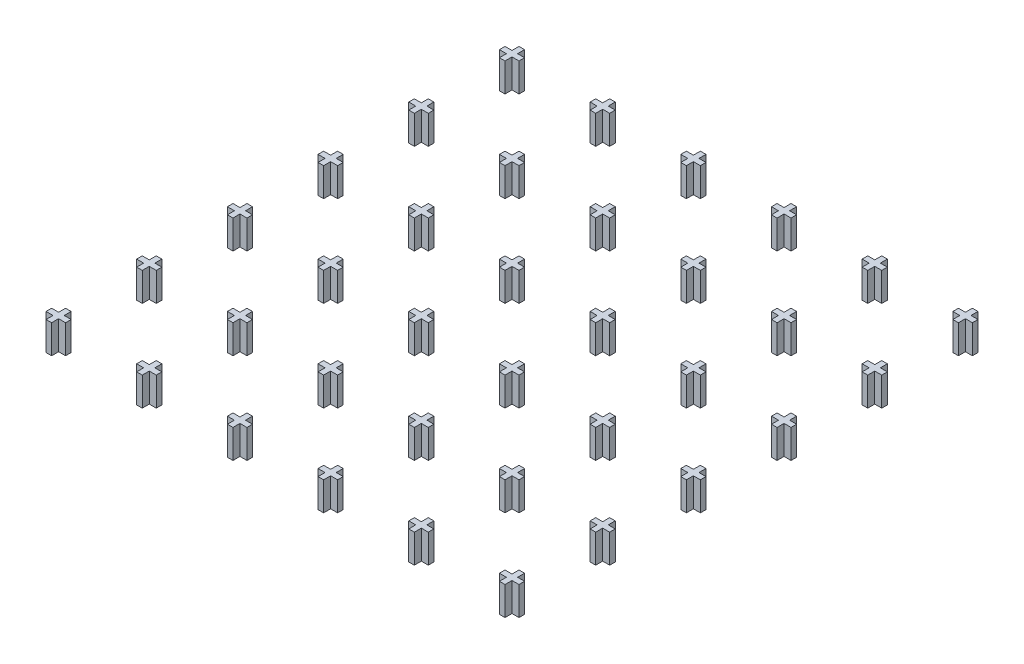
SolidWorks part; units mm, degrees
ref_plane "Front Plane" through (0, 0, 0) normal (0, 0, 1) x (1, 0, 0)
ref_plane "Top Plane" through (0, 0, 0) normal (0, 1, 0) x (1, 0, 0)
ref_plane "Right Plane" through (0, 0, 0) normal (1, 0, 0) x (0, 0, -1)
sketch "Sketch1" plane through (0, 0, 0) normal (0, 1, 0) x (1, 0, 0)
  line L0 (-32.7876, 10.5773) -> (-51.7876, 10.5773) construction
  line L1 (-51.7876, 10.5773) -> (-70.7876, 10.5773) construction
  line L2 (-51.7876, 10.5773) -> (-51.7876, 29.5773) construction
  line L3 (-51.7876, 29.5773) -> (-70.7876, 29.5773) construction
  line L4 (-70.7876, 10.5773) -> (-70.7876, 29.5773) construction
  line L5 (-51.7876, 10.5773) -> (-70.7876, 29.5773) construction
  line L6 (-51.7876, 29.5773) -> (-70.7876, 10.5773) construction
  line L7 (-32.7876, 10.5773) -> (-32.7876, 29.5773) construction
  line L8 (-32.7876, 29.5773) -> (-51.7876, 29.5773) construction
  line L9 (-51.7876, 10.5773) -> (-51.7876, 29.5773) construction
  line L10 (-32.7876, 10.5773) -> (-51.7876, 29.5773) construction
  line L11 (-32.7876, 29.5773) -> (-51.7876, 10.5773) construction
  line L12 (-13.7876, 10.5773) -> (-32.7876, 10.5773) construction
  line L13 (-13.7876, 10.5773) -> (-13.7876, 29.5773) construction
  line L14 (-13.7876, 29.5773) -> (-32.7876, 29.5773) construction
  line L15 (-32.7876, 10.5773) -> (-32.7876, 29.5773) construction
  line L16 (-13.7876, 10.5773) -> (-32.7876, 29.5773) construction
  line L17 (-13.7876, 29.5773) -> (-32.7876, 10.5773) construction
  line L18 (-32.7876, -8.4227) -> (-51.7876, -8.4227) construction
  line L19 (-51.7876, -8.4227) -> (-70.7876, -8.4227) construction
  line L20 (-51.7876, -8.4227) -> (-51.7876, 10.5773) construction
  line L21 (-51.7876, 10.5773) -> (-70.7876, 10.5773) construction
  line L22 (-70.7876, -8.4227) -> (-70.7876, 10.5773) construction
  line L23 (-51.7876, -8.4227) -> (-70.7876, 10.5773) construction
  line L24 (-51.7876, 10.5773) -> (-70.7876, -8.4227) construction
  line L25 (-32.7876, -8.4227) -> (-32.7876, 10.5773) construction
  line L26 (-32.7876, 10.5773) -> (-51.7876, 10.5773) construction
  line L27 (-51.7876, -8.4227) -> (-51.7876, 10.5773) construction
  line L28 (-32.7876, -8.4227) -> (-51.7876, 10.5773) construction
  line L29 (-32.7876, 10.5773) -> (-51.7876, -8.4227) construction
  line L30 (-13.7876, -8.4227) -> (-32.7876, -8.4227) construction
  line L31 (-13.7876, -8.4227) -> (-13.7876, 10.5773) construction
  line L32 (-13.7876, 10.5773) -> (-32.7876, 10.5773) construction
  line L33 (-32.7876, -8.4227) -> (-32.7876, 10.5773) construction
  line L34 (-13.7876, -8.4227) -> (-32.7876, 10.5773) construction
  line L35 (-13.7876, 10.5773) -> (-32.7876, -8.4227) construction
  line L36 (-32.7876, -27.4227) -> (-51.7876, -27.4227) construction
  line L37 (-51.7876, -27.4227) -> (-70.7876, -27.4227) construction
  line L38 (-51.7876, -27.4227) -> (-51.7876, -8.4227) construction
  line L39 (-51.7876, -8.4227) -> (-70.7876, -8.4227) construction
  line L40 (-70.7876, -27.4227) -> (-70.7876, -8.4227) construction
  line L41 (-51.7876, -27.4227) -> (-70.7876, -8.4227) construction
  line L42 (-51.7876, -8.4227) -> (-70.7876, -27.4227) construction
  line L43 (-32.7876, -27.4227) -> (-32.7876, -8.4227) construction
  line L44 (-32.7876, -8.4227) -> (-51.7876, -8.4227) construction
  line L45 (-51.7876, -27.4227) -> (-51.7876, -8.4227) construction
  line L46 (-32.7876, -27.4227) -> (-51.7876, -8.4227) construction
  line L47 (-32.7876, -8.4227) -> (-51.7876, -27.4227) construction
  line L48 (-13.7876, -27.4227) -> (-32.7876, -27.4227) construction
  line L49 (-13.7876, -27.4227) -> (-13.7876, -8.4227) construction
  line L50 (-13.7876, -8.4227) -> (-32.7876, -8.4227) construction
  line L51 (-32.7876, -27.4227) -> (-32.7876, -8.4227) construction
  line L52 (-13.7876, -27.4227) -> (-32.7876, -8.4227) construction
  line L53 (-13.7876, -8.4227) -> (-32.7876, -27.4227) construction
  line L54 (24.2124, 10.5773) -> (5.2124, 10.5773) construction
  line L55 (5.2124, 10.5773) -> (-13.7876, 10.5773) construction
  line L56 (5.2124, 10.5773) -> (5.2124, 29.5773) construction
  line L57 (5.2124, 29.5773) -> (-13.7876, 29.5773) construction
  line L58 (-13.7876, 10.5773) -> (-13.7876, 29.5773) construction
  line L59 (5.2124, 10.5773) -> (-13.7876, 29.5773) construction
  line L60 (5.2124, 29.5773) -> (-13.7876, 10.5773) construction
  line L61 (24.2124, 10.5773) -> (24.2124, 29.5773) construction
  line L62 (24.2124, 29.5773) -> (5.2124, 29.5773) construction
  line L63 (5.2124, 10.5773) -> (5.2124, 29.5773) construction
  line L64 (24.2124, 10.5773) -> (5.2124, 29.5773) construction
  line L65 (24.2124, 29.5773) -> (5.2124, 10.5773) construction
  line L66 (43.2124, 10.5773) -> (24.2124, 10.5773) construction
  line L67 (43.2124, 10.5773) -> (43.2124, 29.5773) construction
  line L68 (43.2124, 29.5773) -> (24.2124, 29.5773) construction
  line L69 (24.2124, 10.5773) -> (24.2124, 29.5773) construction
  line L70 (43.2124, 10.5773) -> (24.2124, 29.5773) construction
  line L71 (43.2124, 29.5773) -> (24.2124, 10.5773) construction
  line L72 (24.2124, -8.4227) -> (5.2124, -8.4227) construction
  line L73 (5.2124, -8.4227) -> (-13.7876, -8.4227) construction
  line L74 (5.2124, -8.4227) -> (5.2124, 10.5773) construction
  line L75 (5.2124, 10.5773) -> (-13.7876, 10.5773) construction
  line L76 (-13.7876, -8.4227) -> (-13.7876, 10.5773) construction
  line L77 (5.2124, -8.4227) -> (-13.7876, 10.5773) construction
  line L78 (5.2124, 10.5773) -> (-13.7876, -8.4227) construction
  line L79 (24.2124, -8.4227) -> (24.2124, 10.5773) construction
  line L80 (24.2124, 10.5773) -> (5.2124, 10.5773) construction
  line L81 (5.2124, -8.4227) -> (5.2124, 10.5773) construction
  line L82 (24.2124, -8.4227) -> (5.2124, 10.5773) construction
  line L83 (24.2124, 10.5773) -> (5.2124, -8.4227) construction
  line L84 (43.2124, -8.4227) -> (24.2124, -8.4227) construction
  line L85 (43.2124, -8.4227) -> (43.2124, 10.5773) construction
  line L86 (43.2124, 10.5773) -> (24.2124, 10.5773) construction
  line L87 (24.2124, -8.4227) -> (24.2124, 10.5773) construction
  line L88 (43.2124, -8.4227) -> (24.2124, 10.5773) construction
  line L89 (43.2124, 10.5773) -> (24.2124, -8.4227) construction
  line L90 (24.2124, -27.4227) -> (5.2124, -27.4227) construction
  line L91 (5.2124, -27.4227) -> (-13.7876, -27.4227) construction
  line L92 (5.2124, -27.4227) -> (5.2124, -8.4227) construction
  line L93 (5.2124, -8.4227) -> (-13.7876, -8.4227) construction
  line L94 (-13.7876, -27.4227) -> (-13.7876, -8.4227) construction
  line L95 (5.2124, -27.4227) -> (-13.7876, -8.4227) construction
  line L96 (5.2124, -8.4227) -> (-13.7876, -27.4227) construction
  line L97 (24.2124, -27.4227) -> (24.2124, -8.4227) construction
  line L98 (24.2124, -8.4227) -> (5.2124, -8.4227) construction
  line L99 (5.2124, -27.4227) -> (5.2124, -8.4227) construction
  line L100 (24.2124, -27.4227) -> (5.2124, -8.4227) construction
  line L101 (24.2124, -8.4227) -> (5.2124, -27.4227) construction
  line L102 (43.2124, -27.4227) -> (24.2124, -27.4227) construction
  line L103 (43.2124, -27.4227) -> (43.2124, -8.4227) construction
  line L104 (43.2124, -8.4227) -> (24.2124, -8.4227) construction
  line L105 (24.2124, -27.4227) -> (24.2124, -8.4227) construction
  line L106 (43.2124, -27.4227) -> (24.2124, -8.4227) construction
  line L107 (43.2124, -8.4227) -> (24.2124, -27.4227) construction
  line L108 (-61.8726, 22.1273) -> (-60.7026, 22.1273)
  line L109 (-60.7026, 22.1273) -> (-60.7026, 20.6623)
  line L110 (-60.7026, 20.6623) -> (-59.2376, 20.6623)
  line L111 (-59.2376, 20.6623) -> (-59.2376, 19.4923)
  line L112 (-59.2376, 19.4923) -> (-60.7026, 19.4923)
  line L113 (-60.7026, 19.4923) -> (-60.7026, 18.0273)
  line L114 (-60.7026, 18.0273) -> (-61.8726, 18.0273)
  line L115 (-61.8726, 18.0273) -> (-61.8726, 19.4923)
  line L116 (-61.8726, 19.4923) -> (-63.3376, 19.4923)
  line L117 (-63.3376, 19.4923) -> (-63.3376, 20.6623)
  line L118 (-63.3376, 20.6623) -> (-61.8726, 20.6623)
  line L119 (-61.8726, 20.6623) -> (-61.8726, 22.1273)
  line L120 (-61.8726, 20.6623) -> (-60.7026, 19.4923) construction
  line L121 (-61.8726, 19.4923) -> (-60.7026, 20.6623) construction
  line L122 (-61.8726, 3.1273) -> (-60.7026, 3.1273)
  line L123 (-60.7026, 3.1273) -> (-60.7026, 1.6623)
  line L124 (-60.7026, 1.6623) -> (-59.2376, 1.6623)
  line L125 (-59.2376, 1.6623) -> (-59.2376, 0.4923)
  line L126 (-59.2376, 0.4923) -> (-60.7026, 0.4923)
  line L127 (-60.7026, 0.4923) -> (-60.7026, -0.9727)
  line L128 (-60.7026, -0.9727) -> (-61.8726, -0.9727)
  line L129 (-61.8726, -0.9727) -> (-61.8726, 0.4923)
  line L130 (-61.8726, 0.4923) -> (-63.3376, 0.4923)
  line L131 (-63.3376, 0.4923) -> (-63.3376, 1.6623)
  line L132 (-63.3376, 1.6623) -> (-61.8726, 1.6623)
  line L133 (-61.8726, 1.6623) -> (-61.8726, 3.1273)
  line L134 (-61.8726, 1.6623) -> (-60.7026, 0.4923) construction
  line L135 (-61.8726, 0.4923) -> (-60.7026, 1.6623) construction
  line L136 (-61.8726, -15.8727) -> (-60.7026, -15.8727)
  line L137 (-60.7026, -15.8727) -> (-60.7026, -17.3377)
  line L138 (-60.7026, -17.3377) -> (-59.2376, -17.3377)
  line L139 (-59.2376, -17.3377) -> (-59.2376, -18.5077)
  line L140 (-59.2376, -18.5077) -> (-60.7026, -18.5077)
  line L141 (-60.7026, -18.5077) -> (-60.7026, -19.9727)
  line L142 (-60.7026, -19.9727) -> (-61.8726, -19.9727)
  line L143 (-61.8726, -19.9727) -> (-61.8726, -18.5077)
  line L144 (-61.8726, -18.5077) -> (-63.3376, -18.5077)
  line L145 (-63.3376, -18.5077) -> (-63.3376, -17.3377)
  line L146 (-63.3376, -17.3377) -> (-61.8726, -17.3377)
  line L147 (-61.8726, -17.3377) -> (-61.8726, -15.8727)
  line L148 (-61.8726, -17.3377) -> (-60.7026, -18.5077) construction
  line L149 (-61.8726, -18.5077) -> (-60.7026, -17.3377) construction
  line L150 (-42.8726, -15.8727) -> (-41.7026, -15.8727)
  line L151 (-41.7026, -15.8727) -> (-41.7026, -17.3377)
  line L152 (-41.7026, -17.3377) -> (-40.2376, -17.3377)
  line L153 (-40.2376, -17.3377) -> (-40.2376, -18.5077)
  line L154 (-40.2376, -18.5077) -> (-41.7026, -18.5077)
  line L155 (-41.7026, -18.5077) -> (-41.7026, -19.9727)
  line L156 (-41.7026, -19.9727) -> (-42.8726, -19.9727)
  line L157 (-42.8726, -19.9727) -> (-42.8726, -18.5077)
  line L158 (-42.8726, -18.5077) -> (-44.3376, -18.5077)
  line L159 (-44.3376, -18.5077) -> (-44.3376, -17.3377)
  line L160 (-44.3376, -17.3377) -> (-42.8726, -17.3377)
  line L161 (-42.8726, -17.3377) -> (-42.8726, -15.8727)
  line L162 (-42.8726, -17.3377) -> (-41.7026, -18.5077) construction
  line L163 (-42.8726, -18.5077) -> (-41.7026, -17.3377) construction
  line L164 (-42.8726, 3.1273) -> (-41.7026, 3.1273)
  line L165 (-41.7026, 3.1273) -> (-41.7026, 1.6623)
  line L166 (-41.7026, 1.6623) -> (-40.2376, 1.6623)
  line L167 (-40.2376, 1.6623) -> (-40.2376, 0.4923)
  line L168 (-40.2376, 0.4923) -> (-41.7026, 0.4923)
  line L169 (-41.7026, 0.4923) -> (-41.7026, -0.9727)
  line L170 (-41.7026, -0.9727) -> (-42.8726, -0.9727)
  line L171 (-42.8726, -0.9727) -> (-42.8726, 0.4923)
  line L172 (-42.8726, 0.4923) -> (-44.3376, 0.4923)
  line L173 (-44.3376, 0.4923) -> (-44.3376, 1.6623)
  line L174 (-44.3376, 1.6623) -> (-42.8726, 1.6623)
  line L175 (-42.8726, 1.6623) -> (-42.8726, 3.1273)
  line L176 (-42.8726, 1.6623) -> (-41.7026, 0.4923) construction
  line L177 (-42.8726, 0.4923) -> (-41.7026, 1.6623) construction
  line L178 (-42.8726, 22.1273) -> (-41.7026, 22.1273)
  line L179 (-41.7026, 22.1273) -> (-41.7026, 20.6623)
  line L180 (-41.7026, 20.6623) -> (-40.2376, 20.6623)
  line L181 (-40.2376, 20.6623) -> (-40.2376, 19.4923)
  line L182 (-40.2376, 19.4923) -> (-41.7026, 19.4923)
  line L183 (-41.7026, 19.4923) -> (-41.7026, 18.0273)
  line L184 (-41.7026, 18.0273) -> (-42.8726, 18.0273)
  line L185 (-42.8726, 18.0273) -> (-42.8726, 19.4923)
  line L186 (-42.8726, 19.4923) -> (-44.3376, 19.4923)
  line L187 (-44.3376, 19.4923) -> (-44.3376, 20.6623)
  line L188 (-44.3376, 20.6623) -> (-42.8726, 20.6623)
  line L189 (-42.8726, 20.6623) -> (-42.8726, 22.1273)
  line L190 (-42.8726, 20.6623) -> (-41.7026, 19.4923) construction
  line L191 (-42.8726, 19.4923) -> (-41.7026, 20.6623) construction
  line L192 (-23.8726, 22.1273) -> (-22.7026, 22.1273)
  line L193 (-22.7026, 22.1273) -> (-22.7026, 20.6623)
  line L194 (-22.7026, 20.6623) -> (-21.2376, 20.6623)
  line L195 (-21.2376, 20.6623) -> (-21.2376, 19.4923)
  line L196 (-21.2376, 19.4923) -> (-22.7026, 19.4923)
  line L197 (-22.7026, 19.4923) -> (-22.7026, 18.0273)
  line L198 (-22.7026, 18.0273) -> (-23.8726, 18.0273)
  line L199 (-23.8726, 18.0273) -> (-23.8726, 19.4923)
  line L200 (-23.8726, 19.4923) -> (-25.3376, 19.4923)
  line L201 (-25.3376, 19.4923) -> (-25.3376, 20.6623)
  line L202 (-25.3376, 20.6623) -> (-23.8726, 20.6623)
  line L203 (-23.8726, 20.6623) -> (-23.8726, 22.1273)
  line L204 (-23.8726, 20.6623) -> (-22.7026, 19.4923) construction
  line L205 (-23.8726, 19.4923) -> (-22.7026, 20.6623) construction
  line L206 (-23.8726, 3.1273) -> (-22.7026, 3.1273)
  line L207 (-22.7026, 3.1273) -> (-22.7026, 1.6623)
  line L208 (-22.7026, 1.6623) -> (-21.2376, 1.6623)
  line L209 (-21.2376, 1.6623) -> (-21.2376, 0.4923)
  line L210 (-21.2376, 0.4923) -> (-22.7026, 0.4923)
  line L211 (-22.7026, 0.4923) -> (-22.7026, -0.9727)
  line L212 (-22.7026, -0.9727) -> (-23.8726, -0.9727)
  line L213 (-23.8726, -0.9727) -> (-23.8726, 0.4923)
  line L214 (-23.8726, 0.4923) -> (-25.3376, 0.4923)
  line L215 (-25.3376, 0.4923) -> (-25.3376, 1.6623)
  line L216 (-25.3376, 1.6623) -> (-23.8726, 1.6623)
  line L217 (-23.8726, 1.6623) -> (-23.8726, 3.1273)
  line L218 (-23.8726, 1.6623) -> (-22.7026, 0.4923) construction
  line L219 (-23.8726, 0.4923) -> (-22.7026, 1.6623) construction
  line L220 (-23.8726, -15.8727) -> (-22.7026, -15.8727)
  line L221 (-22.7026, -15.8727) -> (-22.7026, -17.3377)
  line L222 (-22.7026, -17.3377) -> (-21.2376, -17.3377)
  line L223 (-21.2376, -17.3377) -> (-21.2376, -18.5077)
  line L224 (-21.2376, -18.5077) -> (-22.7026, -18.5077)
  line L225 (-22.7026, -18.5077) -> (-22.7026, -19.9727)
  line L226 (-22.7026, -19.9727) -> (-23.8726, -19.9727)
  line L227 (-23.8726, -19.9727) -> (-23.8726, -18.5077)
  line L228 (-23.8726, -18.5077) -> (-25.3376, -18.5077)
  line L229 (-25.3376, -18.5077) -> (-25.3376, -17.3377)
  line L230 (-25.3376, -17.3377) -> (-23.8726, -17.3377)
  line L231 (-23.8726, -17.3377) -> (-23.8726, -15.8727)
  line L232 (-23.8726, -17.3377) -> (-22.7026, -18.5077) construction
  line L233 (-23.8726, -18.5077) -> (-22.7026, -17.3377) construction
  line L234 (-4.8726, -15.8727) -> (-3.7026, -15.8727)
  line L235 (-3.7026, -15.8727) -> (-3.7026, -17.3377)
  line L236 (-3.7026, -17.3377) -> (-2.2376, -17.3377)
  line L237 (-2.2376, -17.3377) -> (-2.2376, -18.5077)
  line L238 (-2.2376, -18.5077) -> (-3.7026, -18.5077)
  line L239 (-3.7026, -18.5077) -> (-3.7026, -19.9727)
  line L240 (-3.7026, -19.9727) -> (-4.8726, -19.9727)
  line L241 (-4.8726, -19.9727) -> (-4.8726, -18.5077)
  line L242 (-4.8726, -18.5077) -> (-6.3376, -18.5077)
  line L243 (-6.3376, -18.5077) -> (-6.3376, -17.3377)
  line L244 (-6.3376, -17.3377) -> (-4.8726, -17.3377)
  line L245 (-4.8726, -17.3377) -> (-4.8726, -15.8727)
  line L246 (-4.8726, -17.3377) -> (-3.7026, -18.5077) construction
  line L247 (-4.8726, -18.5077) -> (-3.7026, -17.3377) construction
  line L248 (-4.8726, 3.1273) -> (-3.7026, 3.1273)
  line L249 (-3.7026, 3.1273) -> (-3.7026, 1.6623)
  line L250 (-3.7026, 1.6623) -> (-2.2376, 1.6623)
  line L251 (-2.2376, 1.6623) -> (-2.2376, 0.4923)
  line L252 (-2.2376, 0.4923) -> (-3.7026, 0.4923)
  line L253 (-3.7026, 0.4923) -> (-3.7026, -0.9727)
  line L254 (-3.7026, -0.9727) -> (-4.8726, -0.9727)
  line L255 (-4.8726, -0.9727) -> (-4.8726, 0.4923)
  line L256 (-4.8726, 0.4923) -> (-6.3376, 0.4923)
  line L257 (-6.3376, 0.4923) -> (-6.3376, 1.6623)
  line L258 (-6.3376, 1.6623) -> (-4.8726, 1.6623)
  line L259 (-4.8726, 1.6623) -> (-4.8726, 3.1273)
  line L260 (-4.8726, 1.6623) -> (-3.7026, 0.4923) construction
  line L261 (-4.8726, 0.4923) -> (-3.7026, 1.6623) construction
  line L262 (-4.8726, 22.1273) -> (-3.7026, 22.1273)
  line L263 (-3.7026, 22.1273) -> (-3.7026, 20.6623)
  line L264 (-3.7026, 20.6623) -> (-2.2376, 20.6623)
  line L265 (-2.2376, 20.6623) -> (-2.2376, 19.4923)
  line L266 (-2.2376, 19.4923) -> (-3.7026, 19.4923)
  line L267 (-3.7026, 19.4923) -> (-3.7026, 18.0273)
  line L268 (-3.7026, 18.0273) -> (-4.8726, 18.0273)
  line L269 (-4.8726, 18.0273) -> (-4.8726, 19.4923)
  line L270 (-4.8726, 19.4923) -> (-6.3376, 19.4923)
  line L271 (-6.3376, 19.4923) -> (-6.3376, 20.6623)
  line L272 (-6.3376, 20.6623) -> (-4.8726, 20.6623)
  line L273 (-4.8726, 20.6623) -> (-4.8726, 22.1273)
  line L274 (-4.8726, 20.6623) -> (-3.7026, 19.4923) construction
  line L275 (-4.8726, 19.4923) -> (-3.7026, 20.6623) construction
  line L276 (14.1274, 22.1273) -> (15.2974, 22.1273)
  line L277 (15.2974, 22.1273) -> (15.2974, 20.6623)
  line L278 (15.2974, 20.6623) -> (16.7624, 20.6623)
  line L279 (16.7624, 20.6623) -> (16.7624, 19.4923)
  line L280 (16.7624, 19.4923) -> (15.2974, 19.4923)
  line L281 (15.2974, 19.4923) -> (15.2974, 18.0273)
  line L282 (15.2974, 18.0273) -> (14.1274, 18.0273)
  line L283 (14.1274, 18.0273) -> (14.1274, 19.4923)
  line L284 (14.1274, 19.4923) -> (12.6624, 19.4923)
  line L285 (12.6624, 19.4923) -> (12.6624, 20.6623)
  line L286 (12.6624, 20.6623) -> (14.1274, 20.6623)
  line L287 (14.1274, 20.6623) -> (14.1274, 22.1273)
  line L288 (14.1274, 20.6623) -> (15.2974, 19.4923) construction
  line L289 (14.1274, 19.4923) -> (15.2974, 20.6623) construction
  line L290 (14.1274, 3.1273) -> (15.2974, 3.1273)
  line L291 (15.2974, 3.1273) -> (15.2974, 1.6623)
  line L292 (15.2974, 1.6623) -> (16.7624, 1.6623)
  line L293 (16.7624, 1.6623) -> (16.7624, 0.4923)
  line L294 (16.7624, 0.4923) -> (15.2974, 0.4923)
  line L295 (15.2974, 0.4923) -> (15.2974, -0.9727)
  line L296 (15.2974, -0.9727) -> (14.1274, -0.9727)
  line L297 (14.1274, -0.9727) -> (14.1274, 0.4923)
  line L298 (14.1274, 0.4923) -> (12.6624, 0.4923)
  line L299 (12.6624, 0.4923) -> (12.6624, 1.6623)
  line L300 (12.6624, 1.6623) -> (14.1274, 1.6623)
  line L301 (14.1274, 1.6623) -> (14.1274, 3.1273)
  line L302 (14.1274, 1.6623) -> (15.2974, 0.4923) construction
  line L303 (14.1274, 0.4923) -> (15.2974, 1.6623) construction
  line L304 (14.1274, -15.8727) -> (15.2974, -15.8727)
  line L305 (15.2974, -15.8727) -> (15.2974, -17.3377)
  line L306 (15.2974, -17.3377) -> (16.7624, -17.3377)
  line L307 (16.7624, -17.3377) -> (16.7624, -18.5077)
  line L308 (16.7624, -18.5077) -> (15.2974, -18.5077)
  line L309 (15.2974, -18.5077) -> (15.2974, -19.9727)
  line L310 (15.2974, -19.9727) -> (14.1274, -19.9727)
  line L311 (14.1274, -19.9727) -> (14.1274, -18.5077)
  line L312 (14.1274, -18.5077) -> (12.6624, -18.5077)
  line L313 (12.6624, -18.5077) -> (12.6624, -17.3377)
  line L314 (12.6624, -17.3377) -> (14.1274, -17.3377)
  line L315 (14.1274, -17.3377) -> (14.1274, -15.8727)
  line L316 (14.1274, -17.3377) -> (15.2974, -18.5077) construction
  line L317 (14.1274, -18.5077) -> (15.2974, -17.3377) construction
  line L318 (33.1274, -15.8727) -> (34.2974, -15.8727)
  line L319 (34.2974, -15.8727) -> (34.2974, -17.3377)
  line L320 (34.2974, -17.3377) -> (35.7624, -17.3377)
  line L321 (35.7624, -17.3377) -> (35.7624, -18.5077)
  line L322 (35.7624, -18.5077) -> (34.2974, -18.5077)
  line L323 (34.2974, -18.5077) -> (34.2974, -19.9727)
  line L324 (34.2974, -19.9727) -> (33.1274, -19.9727)
  line L325 (33.1274, -19.9727) -> (33.1274, -18.5077)
  line L326 (33.1274, -18.5077) -> (31.6624, -18.5077)
  line L327 (31.6624, -18.5077) -> (31.6624, -17.3377)
  line L328 (31.6624, -17.3377) -> (33.1274, -17.3377)
  line L329 (33.1274, -17.3377) -> (33.1274, -15.8727)
  line L330 (33.1274, -17.3377) -> (34.2974, -18.5077) construction
  line L331 (33.1274, -18.5077) -> (34.2974, -17.3377) construction
  line L332 (33.1274, 3.1273) -> (34.2974, 3.1273)
  line L333 (34.2974, 3.1273) -> (34.2974, 1.6623)
  line L334 (34.2974, 1.6623) -> (35.7624, 1.6623)
  line L335 (35.7624, 1.6623) -> (35.7624, 0.4923)
  line L336 (35.7624, 0.4923) -> (34.2974, 0.4923)
  line L337 (34.2974, 0.4923) -> (34.2974, -0.9727)
  line L338 (34.2974, -0.9727) -> (33.1274, -0.9727)
  line L339 (33.1274, -0.9727) -> (33.1274, 0.4923)
  line L340 (33.1274, 0.4923) -> (31.6624, 0.4923)
  line L341 (31.6624, 0.4923) -> (31.6624, 1.6623)
  line L342 (31.6624, 1.6623) -> (33.1274, 1.6623)
  line L343 (33.1274, 1.6623) -> (33.1274, 3.1273)
  line L344 (33.1274, 1.6623) -> (34.2974, 0.4923) construction
  line L345 (33.1274, 0.4923) -> (34.2974, 1.6623) construction
  line L346 (33.1274, 22.1273) -> (34.2974, 22.1273)
  line L347 (34.2974, 22.1273) -> (34.2974, 20.6623)
  line L348 (34.2974, 20.6623) -> (35.7624, 20.6623)
  line L349 (35.7624, 20.6623) -> (35.7624, 19.4923)
  line L350 (35.7624, 19.4923) -> (34.2974, 19.4923)
  line L351 (34.2974, 19.4923) -> (34.2974, 18.0273)
  line L352 (34.2974, 18.0273) -> (33.1274, 18.0273)
  line L353 (33.1274, 18.0273) -> (33.1274, 19.4923)
  line L354 (33.1274, 19.4923) -> (31.6624, 19.4923)
  line L355 (31.6624, 19.4923) -> (31.6624, 20.6623)
  line L356 (31.6624, 20.6623) -> (33.1274, 20.6623)
  line L357 (33.1274, 20.6623) -> (33.1274, 22.1273)
  line L358 (33.1274, 20.6623) -> (34.2974, 19.4923) construction
  line L359 (33.1274, 19.4923) -> (34.2974, 20.6623) construction
  line L360 (-32.7876, -46.4227) -> (-51.7876, -46.4227) construction
  line L361 (-51.7876, -46.4227) -> (-70.7876, -46.4227) construction
  line L362 (-51.7876, -46.4227) -> (-51.7876, -27.4227) construction
  line L363 (-51.7876, -27.4227) -> (-70.7876, -27.4227) construction
  line L364 (-70.7876, -46.4227) -> (-70.7876, -27.4227) construction
  line L365 (-51.7876, -46.4227) -> (-70.7876, -27.4227) construction
  line L366 (-51.7876, -27.4227) -> (-70.7876, -46.4227) construction
  line L367 (-32.7876, -46.4227) -> (-32.7876, -27.4227) construction
  line L368 (-32.7876, -27.4227) -> (-51.7876, -27.4227) construction
  line L369 (-51.7876, -46.4227) -> (-51.7876, -27.4227) construction
  line L370 (-32.7876, -46.4227) -> (-51.7876, -27.4227) construction
  line L371 (-32.7876, -27.4227) -> (-51.7876, -46.4227) construction
  line L372 (-13.7876, -46.4227) -> (-32.7876, -46.4227) construction
  line L373 (-13.7876, -46.4227) -> (-13.7876, -27.4227) construction
  line L374 (-13.7876, -27.4227) -> (-32.7876, -27.4227) construction
  line L375 (-32.7876, -46.4227) -> (-32.7876, -27.4227) construction
  line L376 (-13.7876, -46.4227) -> (-32.7876, -27.4227) construction
  line L377 (-13.7876, -27.4227) -> (-32.7876, -46.4227) construction
  line L378 (-32.7876, -65.4227) -> (-51.7876, -65.4227) construction
  line L379 (-51.7876, -65.4227) -> (-70.7876, -65.4227) construction
  line L380 (-51.7876, -65.4227) -> (-51.7876, -46.4227) construction
  line L381 (-51.7876, -46.4227) -> (-70.7876, -46.4227) construction
  line L382 (-70.7876, -65.4227) -> (-70.7876, -46.4227) construction
  line L383 (-51.7876, -65.4227) -> (-70.7876, -46.4227) construction
  line L384 (-51.7876, -46.4227) -> (-70.7876, -65.4227) construction
  line L385 (-32.7876, -65.4227) -> (-32.7876, -46.4227) construction
  line L386 (-32.7876, -46.4227) -> (-51.7876, -46.4227) construction
  line L387 (-51.7876, -65.4227) -> (-51.7876, -46.4227) construction
  line L388 (-32.7876, -65.4227) -> (-51.7876, -46.4227) construction
  line L389 (-32.7876, -46.4227) -> (-51.7876, -65.4227) construction
  line L390 (-13.7876, -65.4227) -> (-32.7876, -65.4227) construction
  line L391 (-13.7876, -65.4227) -> (-13.7876, -46.4227) construction
  line L392 (-13.7876, -46.4227) -> (-32.7876, -46.4227) construction
  line L393 (-32.7876, -65.4227) -> (-32.7876, -46.4227) construction
  line L394 (-13.7876, -65.4227) -> (-32.7876, -46.4227) construction
  line L395 (-13.7876, -46.4227) -> (-32.7876, -65.4227) construction
  line L396 (-32.7876, -84.4227) -> (-51.7876, -84.4227) construction
  line L397 (-51.7876, -84.4227) -> (-70.7876, -84.4227) construction
  line L398 (-51.7876, -84.4227) -> (-51.7876, -65.4227) construction
  line L399 (-51.7876, -65.4227) -> (-70.7876, -65.4227) construction
  line L400 (-70.7876, -84.4227) -> (-70.7876, -65.4227) construction
  line L401 (-51.7876, -84.4227) -> (-70.7876, -65.4227) construction
  line L402 (-51.7876, -65.4227) -> (-70.7876, -84.4227) construction
  line L403 (-32.7876, -84.4227) -> (-32.7876, -65.4227) construction
  line L404 (-32.7876, -65.4227) -> (-51.7876, -65.4227) construction
  line L405 (-51.7876, -84.4227) -> (-51.7876, -65.4227) construction
  line L406 (-32.7876, -84.4227) -> (-51.7876, -65.4227) construction
  line L407 (-32.7876, -65.4227) -> (-51.7876, -84.4227) construction
  line L408 (-13.7876, -84.4227) -> (-32.7876, -84.4227) construction
  line L409 (-13.7876, -84.4227) -> (-13.7876, -65.4227) construction
  line L410 (-13.7876, -65.4227) -> (-32.7876, -65.4227) construction
  line L411 (-32.7876, -84.4227) -> (-32.7876, -65.4227) construction
  line L412 (-13.7876, -84.4227) -> (-32.7876, -65.4227) construction
  line L413 (-13.7876, -65.4227) -> (-32.7876, -84.4227) construction
  line L414 (24.2124, -46.4227) -> (5.2124, -46.4227) construction
  line L415 (5.2124, -46.4227) -> (-13.7876, -46.4227) construction
  line L416 (5.2124, -46.4227) -> (5.2124, -27.4227) construction
  line L417 (5.2124, -27.4227) -> (-13.7876, -27.4227) construction
  line L418 (-13.7876, -46.4227) -> (-13.7876, -27.4227) construction
  line L419 (5.2124, -46.4227) -> (-13.7876, -27.4227) construction
  line L420 (5.2124, -27.4227) -> (-13.7876, -46.4227) construction
  line L421 (24.2124, -46.4227) -> (24.2124, -27.4227) construction
  line L422 (24.2124, -27.4227) -> (5.2124, -27.4227) construction
  line L423 (5.2124, -46.4227) -> (5.2124, -27.4227) construction
  line L424 (24.2124, -46.4227) -> (5.2124, -27.4227) construction
  line L425 (24.2124, -27.4227) -> (5.2124, -46.4227) construction
  line L426 (43.2124, -46.4227) -> (24.2124, -46.4227) construction
  line L427 (43.2124, -46.4227) -> (43.2124, -27.4227) construction
  line L428 (43.2124, -27.4227) -> (24.2124, -27.4227) construction
  line L429 (24.2124, -46.4227) -> (24.2124, -27.4227) construction
  line L430 (43.2124, -46.4227) -> (24.2124, -27.4227) construction
  line L431 (43.2124, -27.4227) -> (24.2124, -46.4227) construction
  line L432 (24.2124, -65.4227) -> (5.2124, -65.4227) construction
  line L433 (5.2124, -65.4227) -> (-13.7876, -65.4227) construction
  line L434 (5.2124, -65.4227) -> (5.2124, -46.4227) construction
  line L435 (5.2124, -46.4227) -> (-13.7876, -46.4227) construction
  line L436 (-13.7876, -65.4227) -> (-13.7876, -46.4227) construction
  line L437 (5.2124, -65.4227) -> (-13.7876, -46.4227) construction
  line L438 (5.2124, -46.4227) -> (-13.7876, -65.4227) construction
  line L439 (24.2124, -65.4227) -> (24.2124, -46.4227) construction
  line L440 (24.2124, -46.4227) -> (5.2124, -46.4227) construction
  line L441 (5.2124, -65.4227) -> (5.2124, -46.4227) construction
  line L442 (24.2124, -65.4227) -> (5.2124, -46.4227) construction
  line L443 (24.2124, -46.4227) -> (5.2124, -65.4227) construction
  line L444 (43.2124, -65.4227) -> (24.2124, -65.4227) construction
  line L445 (43.2124, -65.4227) -> (43.2124, -46.4227) construction
  line L446 (43.2124, -46.4227) -> (24.2124, -46.4227) construction
  line L447 (24.2124, -65.4227) -> (24.2124, -46.4227) construction
  line L448 (43.2124, -65.4227) -> (24.2124, -46.4227) construction
  line L449 (43.2124, -46.4227) -> (24.2124, -65.4227) construction
  line L450 (24.2124, -84.4227) -> (5.2124, -84.4227) construction
  line L451 (5.2124, -84.4227) -> (-13.7876, -84.4227) construction
  line L452 (5.2124, -84.4227) -> (5.2124, -65.4227) construction
  line L453 (5.2124, -65.4227) -> (-13.7876, -65.4227) construction
  line L454 (-13.7876, -84.4227) -> (-13.7876, -65.4227) construction
  line L455 (5.2124, -84.4227) -> (-13.7876, -65.4227) construction
  line L456 (5.2124, -65.4227) -> (-13.7876, -84.4227) construction
  line L457 (24.2124, -84.4227) -> (24.2124, -65.4227) construction
  line L458 (24.2124, -65.4227) -> (5.2124, -65.4227) construction
  line L459 (5.2124, -84.4227) -> (5.2124, -65.4227) construction
  line L460 (24.2124, -84.4227) -> (5.2124, -65.4227) construction
  line L461 (24.2124, -65.4227) -> (5.2124, -84.4227) construction
  line L462 (43.2124, -84.4227) -> (24.2124, -84.4227) construction
  line L463 (43.2124, -84.4227) -> (43.2124, -65.4227) construction
  line L464 (43.2124, -65.4227) -> (24.2124, -65.4227) construction
  line L465 (24.2124, -84.4227) -> (24.2124, -65.4227) construction
  line L466 (43.2124, -84.4227) -> (24.2124, -65.4227) construction
  line L467 (43.2124, -65.4227) -> (24.2124, -84.4227) construction
  line L468 (-61.8726, -34.8727) -> (-60.7026, -34.8727)
  line L469 (-60.7026, -34.8727) -> (-60.7026, -36.3377)
  line L470 (-60.7026, -36.3377) -> (-59.2376, -36.3377)
  line L471 (-59.2376, -36.3377) -> (-59.2376, -37.5077)
  line L472 (-59.2376, -37.5077) -> (-60.7026, -37.5077)
  line L473 (-60.7026, -37.5077) -> (-60.7026, -38.9727)
  line L474 (-60.7026, -38.9727) -> (-61.8726, -38.9727)
  line L475 (-61.8726, -38.9727) -> (-61.8726, -37.5077)
  line L476 (-61.8726, -37.5077) -> (-63.3376, -37.5077)
  line L477 (-63.3376, -37.5077) -> (-63.3376, -36.3377)
  line L478 (-63.3376, -36.3377) -> (-61.8726, -36.3377)
  line L479 (-61.8726, -36.3377) -> (-61.8726, -34.8727)
  line L480 (-61.8726, -36.3377) -> (-60.7026, -37.5077) construction
  line L481 (-61.8726, -37.5077) -> (-60.7026, -36.3377) construction
  line L482 (-61.8726, -53.8727) -> (-60.7026, -53.8727)
  line L483 (-60.7026, -53.8727) -> (-60.7026, -55.3377)
  line L484 (-60.7026, -55.3377) -> (-59.2376, -55.3377)
  line L485 (-59.2376, -55.3377) -> (-59.2376, -56.5077)
  line L486 (-59.2376, -56.5077) -> (-60.7026, -56.5077)
  line L487 (-60.7026, -56.5077) -> (-60.7026, -57.9727)
  line L488 (-60.7026, -57.9727) -> (-61.8726, -57.9727)
  line L489 (-61.8726, -57.9727) -> (-61.8726, -56.5077)
  line L490 (-61.8726, -56.5077) -> (-63.3376, -56.5077)
  line L491 (-63.3376, -56.5077) -> (-63.3376, -55.3377)
  line L492 (-63.3376, -55.3377) -> (-61.8726, -55.3377)
  line L493 (-61.8726, -55.3377) -> (-61.8726, -53.8727)
  line L494 (-61.8726, -55.3377) -> (-60.7026, -56.5077) construction
  line L495 (-61.8726, -56.5077) -> (-60.7026, -55.3377) construction
  line L496 (-61.8726, -72.8727) -> (-60.7026, -72.8727)
  line L497 (-60.7026, -72.8727) -> (-60.7026, -74.3377)
  line L498 (-60.7026, -74.3377) -> (-59.2376, -74.3377)
  line L499 (-59.2376, -74.3377) -> (-59.2376, -75.5077)
  line L500 (-59.2376, -75.5077) -> (-60.7026, -75.5077)
  line L501 (-60.7026, -75.5077) -> (-60.7026, -76.9727)
  line L502 (-60.7026, -76.9727) -> (-61.8726, -76.9727)
  line L503 (-61.8726, -76.9727) -> (-61.8726, -75.5077)
  line L504 (-61.8726, -75.5077) -> (-63.3376, -75.5077)
  line L505 (-63.3376, -75.5077) -> (-63.3376, -74.3377)
  line L506 (-63.3376, -74.3377) -> (-61.8726, -74.3377)
  line L507 (-61.8726, -74.3377) -> (-61.8726, -72.8727)
  line L508 (-61.8726, -74.3377) -> (-60.7026, -75.5077) construction
  line L509 (-61.8726, -75.5077) -> (-60.7026, -74.3377) construction
  line L510 (-42.8726, -72.8727) -> (-41.7026, -72.8727)
  line L511 (-41.7026, -72.8727) -> (-41.7026, -74.3377)
  line L512 (-41.7026, -74.3377) -> (-40.2376, -74.3377)
  line L513 (-40.2376, -74.3377) -> (-40.2376, -75.5077)
  line L514 (-40.2376, -75.5077) -> (-41.7026, -75.5077)
  line L515 (-41.7026, -75.5077) -> (-41.7026, -76.9727)
  line L516 (-41.7026, -76.9727) -> (-42.8726, -76.9727)
  line L517 (-42.8726, -76.9727) -> (-42.8726, -75.5077)
  line L518 (-42.8726, -75.5077) -> (-44.3376, -75.5077)
  line L519 (-44.3376, -75.5077) -> (-44.3376, -74.3377)
  line L520 (-44.3376, -74.3377) -> (-42.8726, -74.3377)
  line L521 (-42.8726, -74.3377) -> (-42.8726, -72.8727)
  line L522 (-42.8726, -74.3377) -> (-41.7026, -75.5077) construction
  line L523 (-42.8726, -75.5077) -> (-41.7026, -74.3377) construction
  line L524 (-42.8726, -53.8727) -> (-41.7026, -53.8727)
  line L525 (-41.7026, -53.8727) -> (-41.7026, -55.3377)
  line L526 (-41.7026, -55.3377) -> (-40.2376, -55.3377)
  line L527 (-40.2376, -55.3377) -> (-40.2376, -56.5077)
  line L528 (-40.2376, -56.5077) -> (-41.7026, -56.5077)
  line L529 (-41.7026, -56.5077) -> (-41.7026, -57.9727)
  line L530 (-41.7026, -57.9727) -> (-42.8726, -57.9727)
  line L531 (-42.8726, -57.9727) -> (-42.8726, -56.5077)
  line L532 (-42.8726, -56.5077) -> (-44.3376, -56.5077)
  line L533 (-44.3376, -56.5077) -> (-44.3376, -55.3377)
  line L534 (-44.3376, -55.3377) -> (-42.8726, -55.3377)
  line L535 (-42.8726, -55.3377) -> (-42.8726, -53.8727)
  line L536 (-42.8726, -55.3377) -> (-41.7026, -56.5077) construction
  line L537 (-42.8726, -56.5077) -> (-41.7026, -55.3377) construction
  line L538 (-42.8726, -34.8727) -> (-41.7026, -34.8727)
  line L539 (-41.7026, -34.8727) -> (-41.7026, -36.3377)
  line L540 (-41.7026, -36.3377) -> (-40.2376, -36.3377)
  line L541 (-40.2376, -36.3377) -> (-40.2376, -37.5077)
  line L542 (-40.2376, -37.5077) -> (-41.7026, -37.5077)
  line L543 (-41.7026, -37.5077) -> (-41.7026, -38.9727)
  line L544 (-41.7026, -38.9727) -> (-42.8726, -38.9727)
  line L545 (-42.8726, -38.9727) -> (-42.8726, -37.5077)
  line L546 (-42.8726, -37.5077) -> (-44.3376, -37.5077)
  line L547 (-44.3376, -37.5077) -> (-44.3376, -36.3377)
  line L548 (-44.3376, -36.3377) -> (-42.8726, -36.3377)
  line L549 (-42.8726, -36.3377) -> (-42.8726, -34.8727)
  line L550 (-42.8726, -36.3377) -> (-41.7026, -37.5077) construction
  line L551 (-42.8726, -37.5077) -> (-41.7026, -36.3377) construction
  line L552 (-23.8726, -34.8727) -> (-22.7026, -34.8727)
  line L553 (-22.7026, -34.8727) -> (-22.7026, -36.3377)
  line L554 (-22.7026, -36.3377) -> (-21.2376, -36.3377)
  line L555 (-21.2376, -36.3377) -> (-21.2376, -37.5077)
  line L556 (-21.2376, -37.5077) -> (-22.7026, -37.5077)
  line L557 (-22.7026, -37.5077) -> (-22.7026, -38.9727)
  line L558 (-22.7026, -38.9727) -> (-23.8726, -38.9727)
  line L559 (-23.8726, -38.9727) -> (-23.8726, -37.5077)
  line L560 (-23.8726, -37.5077) -> (-25.3376, -37.5077)
  line L561 (-25.3376, -37.5077) -> (-25.3376, -36.3377)
  line L562 (-25.3376, -36.3377) -> (-23.8726, -36.3377)
  line L563 (-23.8726, -36.3377) -> (-23.8726, -34.8727)
  line L564 (-23.8726, -36.3377) -> (-22.7026, -37.5077) construction
  line L565 (-23.8726, -37.5077) -> (-22.7026, -36.3377) construction
  line L566 (-23.8726, -53.8727) -> (-22.7026, -53.8727)
  line L567 (-22.7026, -53.8727) -> (-22.7026, -55.3377)
  line L568 (-22.7026, -55.3377) -> (-21.2376, -55.3377)
  line L569 (-21.2376, -55.3377) -> (-21.2376, -56.5077)
  line L570 (-21.2376, -56.5077) -> (-22.7026, -56.5077)
  line L571 (-22.7026, -56.5077) -> (-22.7026, -57.9727)
  line L572 (-22.7026, -57.9727) -> (-23.8726, -57.9727)
  line L573 (-23.8726, -57.9727) -> (-23.8726, -56.5077)
  line L574 (-23.8726, -56.5077) -> (-25.3376, -56.5077)
  line L575 (-25.3376, -56.5077) -> (-25.3376, -55.3377)
  line L576 (-25.3376, -55.3377) -> (-23.8726, -55.3377)
  line L577 (-23.8726, -55.3377) -> (-23.8726, -53.8727)
  line L578 (-23.8726, -55.3377) -> (-22.7026, -56.5077) construction
  line L579 (-23.8726, -56.5077) -> (-22.7026, -55.3377) construction
  line L580 (-23.8726, -72.8727) -> (-22.7026, -72.8727)
  line L581 (-22.7026, -72.8727) -> (-22.7026, -74.3377)
  line L582 (-22.7026, -74.3377) -> (-21.2376, -74.3377)
  line L583 (-21.2376, -74.3377) -> (-21.2376, -75.5077)
  line L584 (-21.2376, -75.5077) -> (-22.7026, -75.5077)
  line L585 (-22.7026, -75.5077) -> (-22.7026, -76.9727)
  line L586 (-22.7026, -76.9727) -> (-23.8726, -76.9727)
  line L587 (-23.8726, -76.9727) -> (-23.8726, -75.5077)
  line L588 (-23.8726, -75.5077) -> (-25.3376, -75.5077)
  line L589 (-25.3376, -75.5077) -> (-25.3376, -74.3377)
  line L590 (-25.3376, -74.3377) -> (-23.8726, -74.3377)
  line L591 (-23.8726, -74.3377) -> (-23.8726, -72.8727)
  line L592 (-23.8726, -74.3377) -> (-22.7026, -75.5077) construction
  line L593 (-23.8726, -75.5077) -> (-22.7026, -74.3377) construction
  line L594 (-4.8726, -72.8727) -> (-3.7026, -72.8727)
  line L595 (-3.7026, -72.8727) -> (-3.7026, -74.3377)
  line L596 (-3.7026, -74.3377) -> (-2.2376, -74.3377)
  line L597 (-2.2376, -74.3377) -> (-2.2376, -75.5077)
  line L598 (-2.2376, -75.5077) -> (-3.7026, -75.5077)
  line L599 (-3.7026, -75.5077) -> (-3.7026, -76.9727)
  line L600 (-3.7026, -76.9727) -> (-4.8726, -76.9727)
  line L601 (-4.8726, -76.9727) -> (-4.8726, -75.5077)
  line L602 (-4.8726, -75.5077) -> (-6.3376, -75.5077)
  line L603 (-6.3376, -75.5077) -> (-6.3376, -74.3377)
  line L604 (-6.3376, -74.3377) -> (-4.8726, -74.3377)
  line L605 (-4.8726, -74.3377) -> (-4.8726, -72.8727)
  line L606 (-4.8726, -74.3377) -> (-3.7026, -75.5077) construction
  line L607 (-4.8726, -75.5077) -> (-3.7026, -74.3377) construction
  line L608 (-4.8726, -53.8727) -> (-3.7026, -53.8727)
  line L609 (-3.7026, -53.8727) -> (-3.7026, -55.3377)
  line L610 (-3.7026, -55.3377) -> (-2.2376, -55.3377)
  line L611 (-2.2376, -55.3377) -> (-2.2376, -56.5077)
  line L612 (-2.2376, -56.5077) -> (-3.7026, -56.5077)
  line L613 (-3.7026, -56.5077) -> (-3.7026, -57.9727)
  line L614 (-3.7026, -57.9727) -> (-4.8726, -57.9727)
  line L615 (-4.8726, -57.9727) -> (-4.8726, -56.5077)
  line L616 (-4.8726, -56.5077) -> (-6.3376, -56.5077)
  line L617 (-6.3376, -56.5077) -> (-6.3376, -55.3377)
  line L618 (-6.3376, -55.3377) -> (-4.8726, -55.3377)
  line L619 (-4.8726, -55.3377) -> (-4.8726, -53.8727)
  line L620 (-4.8726, -55.3377) -> (-3.7026, -56.5077) construction
  line L621 (-4.8726, -56.5077) -> (-3.7026, -55.3377) construction
  line L622 (-4.8726, -34.8727) -> (-3.7026, -34.8727)
  line L623 (-3.7026, -34.8727) -> (-3.7026, -36.3377)
  line L624 (-3.7026, -36.3377) -> (-2.2376, -36.3377)
  line L625 (-2.2376, -36.3377) -> (-2.2376, -37.5077)
  line L626 (-2.2376, -37.5077) -> (-3.7026, -37.5077)
  line L627 (-3.7026, -37.5077) -> (-3.7026, -38.9727)
  line L628 (-3.7026, -38.9727) -> (-4.8726, -38.9727)
  line L629 (-4.8726, -38.9727) -> (-4.8726, -37.5077)
  line L630 (-4.8726, -37.5077) -> (-6.3376, -37.5077)
  line L631 (-6.3376, -37.5077) -> (-6.3376, -36.3377)
  line L632 (-6.3376, -36.3377) -> (-4.8726, -36.3377)
  line L633 (-4.8726, -36.3377) -> (-4.8726, -34.8727)
  line L634 (-4.8726, -36.3377) -> (-3.7026, -37.5077) construction
  line L635 (-4.8726, -37.5077) -> (-3.7026, -36.3377) construction
  line L636 (14.1274, -34.8727) -> (15.2974, -34.8727)
  line L637 (15.2974, -34.8727) -> (15.2974, -36.3377)
  line L638 (15.2974, -36.3377) -> (16.7624, -36.3377)
  line L639 (16.7624, -36.3377) -> (16.7624, -37.5077)
  line L640 (16.7624, -37.5077) -> (15.2974, -37.5077)
  line L641 (15.2974, -37.5077) -> (15.2974, -38.9727)
  line L642 (15.2974, -38.9727) -> (14.1274, -38.9727)
  line L643 (14.1274, -38.9727) -> (14.1274, -37.5077)
  line L644 (14.1274, -37.5077) -> (12.6624, -37.5077)
  line L645 (12.6624, -37.5077) -> (12.6624, -36.3377)
  line L646 (12.6624, -36.3377) -> (14.1274, -36.3377)
  line L647 (14.1274, -36.3377) -> (14.1274, -34.8727)
  line L648 (14.1274, -36.3377) -> (15.2974, -37.5077) construction
  line L649 (14.1274, -37.5077) -> (15.2974, -36.3377) construction
  line L650 (14.1274, -53.8727) -> (15.2974, -53.8727)
  line L651 (15.2974, -53.8727) -> (15.2974, -55.3377)
  line L652 (15.2974, -55.3377) -> (16.7624, -55.3377)
  line L653 (16.7624, -55.3377) -> (16.7624, -56.5077)
  line L654 (16.7624, -56.5077) -> (15.2974, -56.5077)
  line L655 (15.2974, -56.5077) -> (15.2974, -57.9727)
  line L656 (15.2974, -57.9727) -> (14.1274, -57.9727)
  line L657 (14.1274, -57.9727) -> (14.1274, -56.5077)
  line L658 (14.1274, -56.5077) -> (12.6624, -56.5077)
  line L659 (12.6624, -56.5077) -> (12.6624, -55.3377)
  line L660 (12.6624, -55.3377) -> (14.1274, -55.3377)
  line L661 (14.1274, -55.3377) -> (14.1274, -53.8727)
  line L662 (14.1274, -55.3377) -> (15.2974, -56.5077) construction
  line L663 (14.1274, -56.5077) -> (15.2974, -55.3377) construction
  line L664 (14.1274, -72.8727) -> (15.2974, -72.8727)
  line L665 (15.2974, -72.8727) -> (15.2974, -74.3377)
  line L666 (15.2974, -74.3377) -> (16.7624, -74.3377)
  line L667 (16.7624, -74.3377) -> (16.7624, -75.5077)
  line L668 (16.7624, -75.5077) -> (15.2974, -75.5077)
  line L669 (15.2974, -75.5077) -> (15.2974, -76.9727)
  line L670 (15.2974, -76.9727) -> (14.1274, -76.9727)
  line L671 (14.1274, -76.9727) -> (14.1274, -75.5077)
  line L672 (14.1274, -75.5077) -> (12.6624, -75.5077)
  line L673 (12.6624, -75.5077) -> (12.6624, -74.3377)
  line L674 (12.6624, -74.3377) -> (14.1274, -74.3377)
  line L675 (14.1274, -74.3377) -> (14.1274, -72.8727)
  line L676 (14.1274, -74.3377) -> (15.2974, -75.5077) construction
  line L677 (14.1274, -75.5077) -> (15.2974, -74.3377) construction
  line L678 (33.1274, -72.8727) -> (34.2974, -72.8727)
  line L679 (34.2974, -72.8727) -> (34.2974, -74.3377)
  line L680 (34.2974, -74.3377) -> (35.7624, -74.3377)
  line L681 (35.7624, -74.3377) -> (35.7624, -75.5077)
  line L682 (35.7624, -75.5077) -> (34.2974, -75.5077)
  line L683 (34.2974, -75.5077) -> (34.2974, -76.9727)
  line L684 (34.2974, -76.9727) -> (33.1274, -76.9727)
  line L685 (33.1274, -76.9727) -> (33.1274, -75.5077)
  line L686 (33.1274, -75.5077) -> (31.6624, -75.5077)
  line L687 (31.6624, -75.5077) -> (31.6624, -74.3377)
  line L688 (31.6624, -74.3377) -> (33.1274, -74.3377)
  line L689 (33.1274, -74.3377) -> (33.1274, -72.8727)
  line L690 (33.1274, -74.3377) -> (34.2974, -75.5077) construction
  line L691 (33.1274, -75.5077) -> (34.2974, -74.3377) construction
  line L692 (33.1274, -53.8727) -> (34.2974, -53.8727)
  line L693 (34.2974, -53.8727) -> (34.2974, -55.3377)
  line L694 (34.2974, -55.3377) -> (35.7624, -55.3377)
  line L695 (35.7624, -55.3377) -> (35.7624, -56.5077)
  line L696 (35.7624, -56.5077) -> (34.2974, -56.5077)
  line L697 (34.2974, -56.5077) -> (34.2974, -57.9727)
  line L698 (34.2974, -57.9727) -> (33.1274, -57.9727)
  line L699 (33.1274, -57.9727) -> (33.1274, -56.5077)
  line L700 (33.1274, -56.5077) -> (31.6624, -56.5077)
  line L701 (31.6624, -56.5077) -> (31.6624, -55.3377)
  line L702 (31.6624, -55.3377) -> (33.1274, -55.3377)
  line L703 (33.1274, -55.3377) -> (33.1274, -53.8727)
  line L704 (33.1274, -55.3377) -> (34.2974, -56.5077) construction
  line L705 (33.1274, -56.5077) -> (34.2974, -55.3377) construction
  line L706 (33.1274, -34.8727) -> (34.2974, -34.8727)
  line L707 (34.2974, -34.8727) -> (34.2974, -36.3377)
  line L708 (34.2974, -36.3377) -> (35.7624, -36.3377)
  line L709 (35.7624, -36.3377) -> (35.7624, -37.5077)
  line L710 (35.7624, -37.5077) -> (34.2974, -37.5077)
  line L711 (34.2974, -37.5077) -> (34.2974, -38.9727)
  line L712 (34.2974, -38.9727) -> (33.1274, -38.9727)
  line L713 (33.1274, -38.9727) -> (33.1274, -37.5077)
  line L714 (33.1274, -37.5077) -> (31.6624, -37.5077)
  line L715 (31.6624, -37.5077) -> (31.6624, -36.3377)
  line L716 (31.6624, -36.3377) -> (33.1274, -36.3377)
  line L717 (33.1274, -36.3377) -> (33.1274, -34.8727)
  line L718 (33.1274, -36.3377) -> (34.2974, -37.5077) construction
  line L719 (33.1274, -37.5077) -> (34.2974, -36.3377) construction
  point P0 (-61.2876, 20.0773)
  point P6 (-42.2876, 20.0773)
  point P7 (-23.2876, 20.0773)
  point P13 (-61.2876, 1.0773)
  point P18 (-61.2876, -17.9227)
  point P22 (-42.2876, 1.0773)
  point P23 (-23.2876, 1.0773)
  point P31 (-4.2876, 20.0773)
  point P35 (-42.2876, -17.9227)
  point P36 (-23.2876, -17.9227)
  point P44 (-4.2876, 1.0773)
  point P48 (14.7124, 20.0773)
  point P49 (33.7124, 20.0773)
  point P57 (-4.2876, -17.9227)
  point P61 (14.7124, 1.0773)
  point P62 (33.7124, 1.0773)
  point P75 (14.7124, -17.9227)
  point P76 (33.7124, -17.9227)
  point P289 (-61.2876, 20.0773)
  point P290 (-42.2876, 20.0773)
  point P291 (-42.2876, 1.0773)
  point P292 (-61.2876, 1.0773)
  point P293 (-61.2876, -17.9227)
  point P294 (-42.2876, -17.9227)
  point P295 (-23.2876, 20.0773)
  point P296 (-23.2876, 1.0773)
  point P297 (-23.2876, -17.9227)
  point P298 (-4.2876, -17.9227)
  point P299 (-4.2876, 1.0773)
  point P300 (-4.2876, 20.0773)
  point P301 (14.7124, 20.0773)
  point P302 (33.7124, 20.0773)
  point P303 (33.7124, 1.0773)
  point P304 (14.7124, 1.0773)
  point P305 (14.7124, -17.9227)
  point P306 (33.7124, -17.9227)
  point P307 (-61.2876, -36.9227)
  point P313 (-42.2876, -36.9227)
  point P314 (-23.2876, -36.9227)
  point P320 (-61.2876, -55.9227)
  point P325 (-61.2876, -74.9227)
  point P329 (-42.2876, -55.9227)
  point P330 (-23.2876, -55.9227)
  point P338 (-4.2876, -36.9227)
  point P342 (-42.2876, -74.9227)
  point P343 (-23.2876, -74.9227)
  point P351 (-4.2876, -55.9227)
  point P355 (14.7124, -36.9227)
  point P356 (33.7124, -36.9227)
  point P364 (-4.2876, -74.9227)
  point P368 (14.7124, -55.9227)
  point P369 (33.7124, -55.9227)
  point P382 (14.7124, -74.9227)
  point P383 (33.7124, -74.9227)
  point P596 (-61.2876, -36.9227)
  point P597 (-42.2876, -36.9227)
  point P598 (-42.2876, -55.9227)
  point P599 (-61.2876, -55.9227)
  point P600 (-61.2876, -74.9227)
  point P601 (-42.2876, -74.9227)
  point P602 (-23.2876, -36.9227)
  point P603 (-23.2876, -55.9227)
  point P604 (-23.2876, -74.9227)
  point P605 (-4.2876, -74.9227)
  point P606 (-4.2876, -55.9227)
  point P607 (-4.2876, -36.9227)
  point P608 (14.7124, -36.9227)
  point P609 (33.7124, -36.9227)
  point P610 (33.7124, -55.9227)
  point P611 (14.7124, -55.9227)
  point P612 (14.7124, -74.9227)
  point P613 (33.7124, -74.9227)
  dimension "D1" = 19
  dimension "D2" = 1.17
  dimension "D3" = 4.1
  dimension "D4" = 1.17
  dimension "D5" = 4.1
  dimension "D6" = 1.17
  dimension "D7" = 4.1
  dimension "D8" = 1.17
  dimension "D9" = 4.1
  dimension "D10" = 1.17
  dimension "D11" = 4.1
  dimension "D12" = 1.17
  dimension "D13" = 4.1
  dimension "D14" = 1.17
  dimension "D15" = 4.1
  dimension "D16" = 1.17
  dimension "D17" = 4.1
  dimension "D18" = 1.17
  dimension "D19" = 4.1
  dimension "D20" = 1.17
  dimension "D21" = 4.1
  dimension "D22" = 1.17
  dimension "D23" = 4.1
  dimension "D24" = 1.17
  dimension "D25" = 4.1
  dimension "D26" = 1.17
  dimension "D27" = 4.1
  dimension "D28" = 1.17
  dimension "D29" = 4.1
  dimension "D30" = 1.17
  dimension "D31" = 4.1
  dimension "D32" = 1.17
  dimension "D33" = 4.1
  dimension "D34" = 1.17
  dimension "D35" = 4.1
  dimension "D36" = 1.17
  dimension "D37" = 4.1
  dimension "D38" = 19
  dimension "D39" = 1.17
  dimension "D40" = 4.1
  dimension "D41" = 1.17
  dimension "D42" = 4.1
  dimension "D43" = 1.17
  dimension "D44" = 4.1
  dimension "D45" = 1.17
  dimension "D46" = 4.1
  dimension "D47" = 1.17
  dimension "D48" = 4.1
  dimension "D49" = 1.17
  dimension "D50" = 4.1
  dimension "D51" = 1.17
  dimension "D52" = 4.1
  dimension "D53" = 1.17
  dimension "D54" = 4.1
  dimension "D55" = 1.17
  dimension "D56" = 4.1
  dimension "D57" = 1.17
  dimension "D58" = 4.1
  dimension "D59" = 1.17
  dimension "D60" = 4.1
  dimension "D61" = 1.17
  dimension "D62" = 4.1
  dimension "D63" = 1.17
  dimension "D64" = 4.1
  dimension "D65" = 1.17
  dimension "D66" = 4.1
  dimension "D67" = 1.17
  dimension "D68" = 4.1
  dimension "D69" = 1.17
  dimension "D70" = 4.1
  dimension "D71" = 1.17
  dimension "D72" = 4.1
  dimension "D73" = 1.17
  dimension "D74" = 4.1
extrude "Boss-Extrude1" add sketch "Sketch1" along normal blind 6
